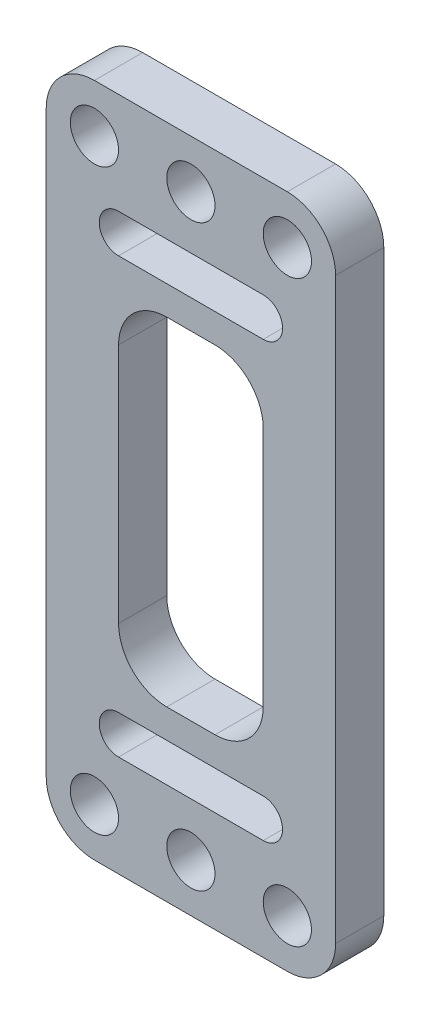
SolidWorks part; units mm, degrees
ref_plane "Front Plane" through (0, 0, 0) normal (0, 0, 1) x (1, 0, 0)
ref_plane "Top Plane" through (0, 0, 0) normal (0, 1, 0) x (1, 0, 0)
ref_plane "Right Plane" through (0, 0, 0) normal (1, 0, 0) x (0, 0, -1)
sketch "Sketch1" plane through (0, 0, 0) normal (0, 0, 1) x (1, 0, 0)
  line L0 (0, 0) -> (0, 30) construction
  line L1 (-15, -35) -> (15, -35)
  line L2 (-15, -35) -> (-15, 35)
  line L3 (-15, 35) -> (15, 35)
  line L4 (15, -35) -> (15, 35)
  line L5 (-15, -35) -> (15, 35) construction
  line L6 (-15, 35) -> (15, -35) construction
  line L7 (0, 30) -> (10, 30) construction
  line L8 (0, 0) -> (15, 0) construction
  line L9 (0, 0) -> (-15, 0) construction
  circle A0 centre (0, 30) radius 2.5
  circle A1 centre (10, 30) radius 2.5
  circle A2 centre (-10, 30) radius 2.5
  circle A3 centre (10, -30) radius 2.5
  circle A4 centre (0, -30) radius 2.5
  circle A5 centre (-10, -30) radius 2.5
  point P0 (0, 0)
  dimension "D3" = 5
  dimension "D6" = 5
  dimension "D1" = 30
  dimension "D2" = 70
  dimension "D4" = 10
  dimension "D5" = 30
extrude "Boss-Extrude1" add sketch "Sketch1" along normal blind 5
fillet "Fillet1" radius 5 4 edges at (15, -35, 2.5) (-15, -35, 2.5) (15, 35, 2.5) (-15, 35, 2.5)
sketch "Sketch2" plane through (0, 0, 5) normal (0, 0, 1) x (1, 0, 0)
  line L1 (-7.5, -17.5) -> (7.5, -17.5)
  line L2 (-7.5, -17.5) -> (-7.5, 17.5)
  line L3 (-7.5, 17.5) -> (7.5, 17.5)
  line L4 (7.5, -17.5) -> (7.5, 17.5)
  line L5 (-7.5, -17.5) -> (7.5, 17.5) construction
  line L6 (-7.5, 17.5) -> (7.5, -17.5) construction
  point P0 (0, 0)
  dimension "D1" = 15
  dimension "D2" = 35
extrude "Cut-Extrude1" cut sketch "Sketch2" against normal through all
sketch "Sketch3" plane through (0, 0, 5) normal (0, 0, 1) x (1, 0, 0)
  line L0 (0, 0) -> (0, 22.5) construction
  line L1 (-7.5, 22.5) -> (7.5, 22.5) construction
  line L2 (-7.5, 24.5) -> (7.5, 24.5)
  line L3 (-7.5, 20.5) -> (7.5, 20.5)
  line L4 (0, 0) -> (15, 0) construction
  line L5 (15, -30) -> (15, 30) construction
  line L6 (-7.5, -22.5) -> (7.5, -22.5) construction
  line L7 (-7.5, -24.5) -> (7.5, -24.5)
  line L8 (-7.5, -20.5) -> (7.5, -20.5)
  arc A1 (-7.5, 24.5) -> (-7.5, 20.5) centre (-7.5, 22.5) ccw
  arc A2 (7.5, 20.5) -> (7.5, 24.5) centre (7.5, 22.5) ccw
  arc A3 (-7.5, -24.5) -> (-7.5, -20.5) centre (-7.5, -22.5) cw
  arc A4 (7.5, -20.5) -> (7.5, -24.5) centre (7.5, -22.5) cw
  point P5 (0, 22.5)
  point P15 (0, -22.5)
  dimension "D2" = 2
  dimension "D1" = 15
  dimension "D3" = 22.5
extrude "Cut-Extrude2" cut sketch "Sketch3" against normal through all
fillet "Fillet2" radius 5 4 edges at (7.5, -17.5, 2.5) (-7.5, -17.5, 2.5) (7.5, 17.5, 2.5) (-7.5, 17.5, 2.5)
